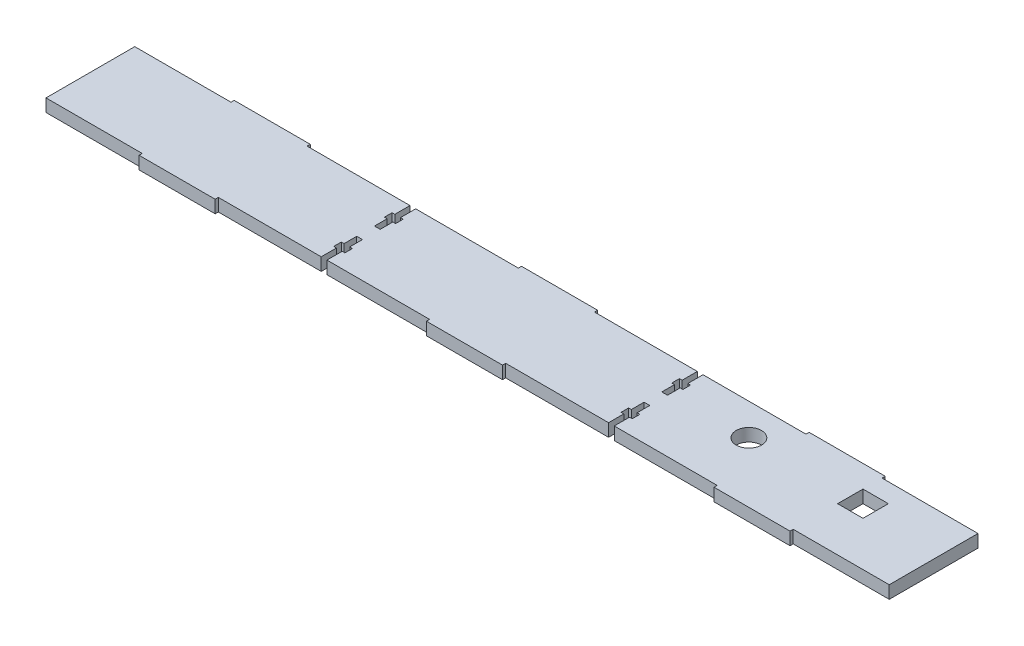
SolidWorks part; units mm, degrees
ref_plane "Front Plane" through (0, 0, 0) normal (0, 0, 1) x (1, 0, 0)
ref_plane "Top Plane" through (0, 0, 0) normal (0, 1, 0) x (1, 0, 0)
ref_plane "Right Plane" through (0, 0, 0) normal (1, 0, 0) x (0, 0, -1)
sketch "Sketch1" plane through (0, 0, 0) normal (0, 1, 0) x (1, 0, 0)
  line L1 (214.3125, -23.8125) -> (-214.3125, -23.8125)
  line L2 (214.3125, -23.8125) -> (214.3125, 23.8125)
  line L3 (214.3125, 23.8125) -> (-214.3125, 23.8125)
  line L4 (-214.3125, -23.8125) -> (-214.3125, 23.8125)
  line L5 (214.3125, -23.8125) -> (-214.3125, 23.8125) construction
  line L6 (214.3125, 23.8125) -> (-214.3125, -23.8125) construction
  point P0 (0, 0)
  dimension "D1" = 428.625
  dimension "D2" = 47.625
extrude "Boss-Extrude1" add sketch "Sketch1" along normal blind 6.35
sketch "Sketch2" plane through (0, 0, 0) normal (0, -1, 0) x (1, 0, 0)
  line L0 (73.6243, -22.225) -> (70.6477, -22.225) construction
  line L1 (-70.3937, -22.225) -> (-73.3703, -22.225) construction
  line L2 (-73.3108, 4.445) -> (-73.3108, 10.795)
  line L3 (-73.3108, 10.795) -> (-74.676, 10.795)
  line L4 (73.6243, -22.225) -> (70.6477, -22.225) construction
  line L5 (-70.3937, -22.225) -> (-73.3703, -22.225) construction
  line L6 (-162.941, 22.225) -> (-214.3125, 22.225)
  line L7 (-214.3125, -23.8125) -> (-214.3125, 23.8125) construction
  line L8 (163.068, 22.225) -> (163.068, 23.8125) construction
  line L9 (-162.941, 22.225) -> (-162.941, 23.8125) construction
  line L10 (-162.941, 23.8125) -> (-124.841, 23.8125) construction
  line L11 (-162.941, 22.225) -> (-124.841, 22.225) construction
  line L12 (-124.841, 22.225) -> (-124.841, 23.8125) construction
  line L13 (-19.05, 22.225) -> (-19.05, 23.8125) construction
  line L14 (-19.05, 23.8125) -> (19.05, 23.8125) construction
  line L15 (-19.05, 22.225) -> (19.05, 22.225) construction
  line L16 (19.05, 22.225) -> (19.05, 23.8125) construction
  line L17 (124.968, 22.225) -> (163.068, 22.225) construction
  line L18 (124.968, 23.8125) -> (163.068, 23.8125) construction
  line L19 (124.968, 22.225) -> (124.968, 23.8125) construction
  line L20 (163.068, 22.225) -> (163.068, 23.8125)
  line L21 (124.968, 22.225) -> (163.068, 22.225)
  line L22 (124.968, 23.8125) -> (163.068, 23.8125)
  line L23 (124.968, 22.225) -> (124.968, 23.8125)
  line L24 (19.05, 22.225) -> (19.05, 23.8125)
  line L25 (-19.05, 22.225) -> (19.05, 22.225)
  line L26 (-19.05, 23.8125) -> (19.05, 23.8125)
  line L27 (-19.05, 22.225) -> (-19.05, 23.8125)
  line L28 (-124.841, 22.225) -> (-124.841, 23.8125)
  line L29 (-162.941, 22.225) -> (-124.841, 22.225)
  line L30 (-162.941, 23.8125) -> (-124.841, 23.8125)
  line L31 (-162.941, 22.225) -> (-162.941, 23.8125)
  line L32 (-214.3125, 22.225) -> (-214.3125, 23.8125)
  line L33 (-214.3125, 23.8125) -> (-162.941, 23.8125)
  line L34 (-124.841, 23.8125) -> (-19.05, 23.8125)
  line L35 (-124.841, 22.225) -> (-19.05, 22.225)
  line L36 (19.05, 22.225) -> (124.968, 22.225)
  line L37 (124.968, 23.8125) -> (19.05, 23.8125)
  line L38 (163.068, 22.225) -> (214.3125, 22.225)
  line L39 (214.3125, 23.8125) -> (214.3125, -23.8125) construction
  line L40 (214.3125, 22.225) -> (214.3125, 23.8125)
  line L41 (214.3125, 23.8125) -> (163.068, 23.8125)
  line L42 (-214.3125, 0) -> (214.3125, 0) construction
  line L43 (214.3125, -22.225) -> (214.3125, -23.8125)
  line L44 (163.068, -22.225) -> (163.068, -23.8125)
  line L45 (214.3125, -23.8125) -> (163.068, -23.8125)
  line L46 (163.068, -22.225) -> (214.3125, -22.225)
  line L47 (124.968, -22.225) -> (124.968, -23.8125)
  line L48 (19.05, -22.225) -> (19.05, -23.8125)
  line L49 (124.968, -23.8125) -> (19.05, -23.8125)
  line L50 (19.05, -22.225) -> (124.968, -22.225)
  line L51 (-19.05, -22.225) -> (-19.05, -23.8125)
  line L52 (-124.841, -23.8125) -> (-19.05, -23.8125)
  line L53 (-124.841, -22.225) -> (-124.841, -23.8125)
  line L54 (-124.841, -22.225) -> (-19.05, -22.225)
  line L55 (-162.941, -22.225) -> (-162.941, -23.8125)
  line L56 (-214.3125, -22.225) -> (-214.3125, -23.8125)
  line L57 (-214.3125, -23.8125) -> (-162.941, -23.8125)
  line L58 (-162.941, -22.225) -> (-214.3125, -22.225)
  line L59 (-162.941, 22.225) -> (-162.941, 23.8125)
  line L60 (-162.941, 22.225) -> (-162.941, 23.8125)
  line L61 (-162.941, 22.225) -> (-214.3125, 22.225)
  line L62 (-214.3125, 23.8125) -> (-162.941, 23.8125)
  line L75 (-71.882, 22.225) -> (-71.882, 4.445) construction
  line L83 (-74.676, 10.795) -> (-74.676, 14.605)
  line L84 (-74.676, 14.605) -> (-73.3108, 14.605)
  line L85 (-73.3108, 14.605) -> (-73.3108, 22.225)
  line L86 (-73.3108, 22.225) -> (-70.4533, 22.225)
  line L87 (-70.4533, 4.445) -> (-73.3108, 4.445)
  line L88 (-70.4533, 4.445) -> (-70.4533, 10.795)
  line L89 (-70.4533, 10.795) -> (-69.088, 10.795)
  line L90 (-69.088, 10.795) -> (-69.088, 14.605)
  line L91 (-69.088, 14.605) -> (-70.4533, 14.605)
  line L92 (-70.4533, 14.605) -> (-70.4533, 22.225)
  line L93 (73.4377, 4.445) -> (70.5802, 4.445)
  line L94 (70.5802, 4.445) -> (70.5802, 10.795)
  line L95 (70.5802, 10.795) -> (69.215, 10.795)
  line L96 (69.215, 10.795) -> (69.215, 14.605)
  line L97 (69.215, 14.605) -> (70.5802, 14.605)
  line L98 (70.5802, 14.605) -> (70.5802, 22.225)
  line L99 (70.5802, 22.225) -> (73.4377, 22.225)
  line L100 (73.4377, 14.605) -> (73.4377, 22.225)
  line L101 (74.803, 14.605) -> (73.4377, 14.605)
  line L102 (74.803, 10.795) -> (74.803, 14.605)
  line L103 (73.4377, 10.795) -> (74.803, 10.795)
  line L104 (73.4377, 4.445) -> (73.4377, 10.795)
  line L105 (72.009, 22.225) -> (72.009, 4.445) construction
  line L106 (72.009, 13.335) -> (-71.882, 13.335) construction
  line L107 (73.4377, -4.445) -> (73.4377, -10.795)
  line L108 (73.4377, -10.795) -> (74.803, -10.795)
  line L109 (74.803, -10.795) -> (74.803, -14.605)
  line L110 (74.803, -14.605) -> (73.4377, -14.605)
  line L111 (73.4377, -14.605) -> (73.4377, -22.225)
  line L112 (70.5802, -22.225) -> (73.4377, -22.225)
  line L113 (70.5802, -14.605) -> (70.5802, -22.225)
  line L114 (69.215, -14.605) -> (70.5802, -14.605)
  line L115 (69.215, -10.795) -> (69.215, -14.605)
  line L116 (70.5802, -10.795) -> (69.215, -10.795)
  line L117 (70.5802, -4.445) -> (70.5802, -10.795)
  line L118 (73.4377, -4.445) -> (70.5802, -4.445)
  line L119 (-70.4533, -4.445) -> (-70.4533, -10.795)
  line L120 (-70.4533, -10.795) -> (-69.088, -10.795)
  line L121 (-69.088, -10.795) -> (-69.088, -14.605)
  line L122 (-69.088, -14.605) -> (-70.4533, -14.605)
  line L123 (-70.4533, -14.605) -> (-70.4533, -22.225)
  line L124 (-73.3108, -22.225) -> (-70.4533, -22.225)
  line L125 (-73.3108, -14.605) -> (-73.3108, -22.225)
  line L126 (-74.676, -14.605) -> (-73.3108, -14.605)
  line L127 (-74.676, -10.795) -> (-74.676, -14.605)
  line L128 (-73.3108, -10.795) -> (-74.676, -10.795)
  line L129 (-73.3108, -4.445) -> (-73.3108, -10.795)
  line L130 (-70.4533, -4.445) -> (-73.3108, -4.445)
  point P11 (-71.882, 23.8125)
  point P12 (72.136, 23.8125)
  point P78 (72.009, 4.445)
  line M5 (-214.3125, 23.8125) -> (-214.3125, -23.8125)
  line M6 (-214.3125, -23.8125) -> (214.3125, -23.8125)
  line M7 (214.3125, -23.8125) -> (214.3125, 23.8125)
  line M8 (214.3125, 23.8125) -> (-214.3125, 23.8125)
  dimension "D1" = 1.4287
  dimension "D2" = 17.78
  dimension "D3" = 3.81
  dimension "D4" = 5.588
  dimension "D5" = 7.62
  dimension "D6" = 2
extrude "Cut-Extrude4" cut sketch "Sketch2" against normal up to surface (6.35 mm away) contours L54 L53 L51 M6 | L20 L38 M7 M8 | L24 L36 L23 M8 | L28 L35 L27 M8 | L50 L48 L47 M6 | L46 L44 M6 M7 | L6 L31 M8 M5 | L55 L58 M5 M6 | L119 L120 L121 L122 L123 L124 L125 L126 L127 L128 L129 L130 | L87 L2 L3 L83 L84 L85 L86 L92 L91 L90 L89 L88 | L93 L94 L95 L96 L97 L98 L99 L100 L101 L102 L103 L104 | L107 L108 L109 L110 L111 L112 L113 L114 L115 L116 L117 L118 up to face at (0, 6.35, 0)
sketch "Sketch3" plane through (0, 0, 0) normal (0, -1, 0) x (1, 0, 0)
  line L0 (-214.3125, 0) -> (214.3125, 0) construction
  line L1 (-214.3125, -22.225) -> (-214.3125, 22.225) construction
  line L2 (214.3125, 22.225) -> (214.3125, -22.225) construction
  line L3 (-143.891, 23.8125) -> (-143.891, -23.8125) construction
  line L4 (-162.941, 23.8125) -> (-124.841, 23.8125) construction
  line L5 (-124.841, -23.8125) -> (-162.941, -23.8125) construction
  line L7 (112.268, -6.35) -> (175.768, -6.35) construction
  line L9 (144.018, 23.8125) -> (144.018, -23.8125) construction
  line L10 (124.968, 23.8125) -> (163.068, 23.8125) construction
  line L11 (163.068, -23.8125) -> (124.968, -23.8125) construction
  line L13 (-214.3125, -6.35) -> (214.3125, -6.35) construction
  line L15 (19.05, -22.225) -> (70.5802, -22.225) construction
  line L16 (0, 23.8125) -> (0, -23.8125) construction
  line L17 (-19.05, 23.8125) -> (19.05, 23.8125) construction
  line L18 (19.05, -23.8125) -> (-19.05, -23.8125) construction
  line L20 (163.068, 0) -> (175.768, 0)
  line L21 (163.068, 0) -> (163.068, -12.7)
  line L22 (163.068, -12.7) -> (175.768, -12.7)
  line L23 (175.768, 0) -> (175.768, -12.7)
  circle A0 centre (-143.891, -6.35) radius 6.35 construction
  circle A1 centre (0, -6.35) radius 6.35 construction
  circle A2 centre (112.268, -6.35) radius 6.35
  point P33 (163.068, -6.35)
  point P41 (144.018, -6.35)
  dimension "D1" = 12.7
  dimension "D2" = 15.875
  dimension "D3" = 12.7
  dimension "D4" = 63.5
sketch "Sketch4" plane through (0, 0, 0) normal (0, -1, 0) x (1, 0, 0)
  line L11 (-214.3125, 0) -> (214.3125, 0) construction
  line L12 (-162.941, -22.225) -> (-214.3125, -22.225) construction
  line L13 (-214.3125, 22.225) -> (-211.1375, 22.225)
  line L14 (-214.3125, 22.225) -> (-214.3125, -22.225)
  line L15 (-214.3125, -22.225) -> (-211.1375, -22.225)
  line L16 (-211.1375, 22.225) -> (-211.1375, -22.225)
  line L21 (-214.3125, 0) -> (214.3125, 0) construction
  line L22 (0, -23.8125) -> (0, 23.8125) construction
  line L23 (-19.05, 23.8125) -> (19.05, 23.8125) construction
  line L24 (214.3125, -22.225) -> (211.1375, -22.225)
  line L25 (211.1375, 22.225) -> (211.1375, -22.225)
  line L26 (214.3125, 22.225) -> (211.1375, 22.225)
  line L27 (214.3125, 22.225) -> (214.3125, -22.225)
  point P16 (0, 0)
  dimension "D1" = 3.175
extrude "Cut-Extrude5" cut sketch "Sketch4" against normal up to surface (6.35 mm away) up to face at (0.0535, 6.35, 0)
extrude "Cut-Extrude6" cut sketch "Sketch3" against normal up to surface (6.35 mm away) up to face at (0.0535, 6.35, 0)
sketch "Sketch5" plane through (0, 0, 0) normal (0, -1, 0) x (1, 0, 0)
  line L0 (175.768, -12.7) -> (175.768, 0) construction
  line L1 (163.068, -12.7) -> (175.768, -12.7) construction
  line L2 (163.068, 0) -> (163.068, -12.7) construction
  line L3 (175.768, 0) -> (163.068, 0) construction
  line L4 (175.768, -12.7) -> (175.768, 0)
  line L5 (163.068, -12.7) -> (175.768, -12.7)
  line L6 (163.068, 0) -> (163.068, -12.7)
  line L7 (175.768, 0) -> (163.068, 0)
  line L8 (73.4377, -22.225) -> (124.968, -22.225) construction
  line L9 (211.1375, 22.225) -> (211.1375, -22.225) construction
  circle A0 centre (112.268, -6.35) radius 6.35 construction
  circle A1 centre (112.268, -6.35) radius 6.35
  dimension "D1" = 12.7
  dimension "D2" = 12.7
  dimension "D3" = 15.875
  dimension "D4" = 9.525
  dimension "D5" = 98.8695
  dimension "D6" = 48.0695
equation "\"sheetthickness\"= 1 / 4"
equation "\"D1@Boss-Extrude1\"=\"sheetthickness\""
